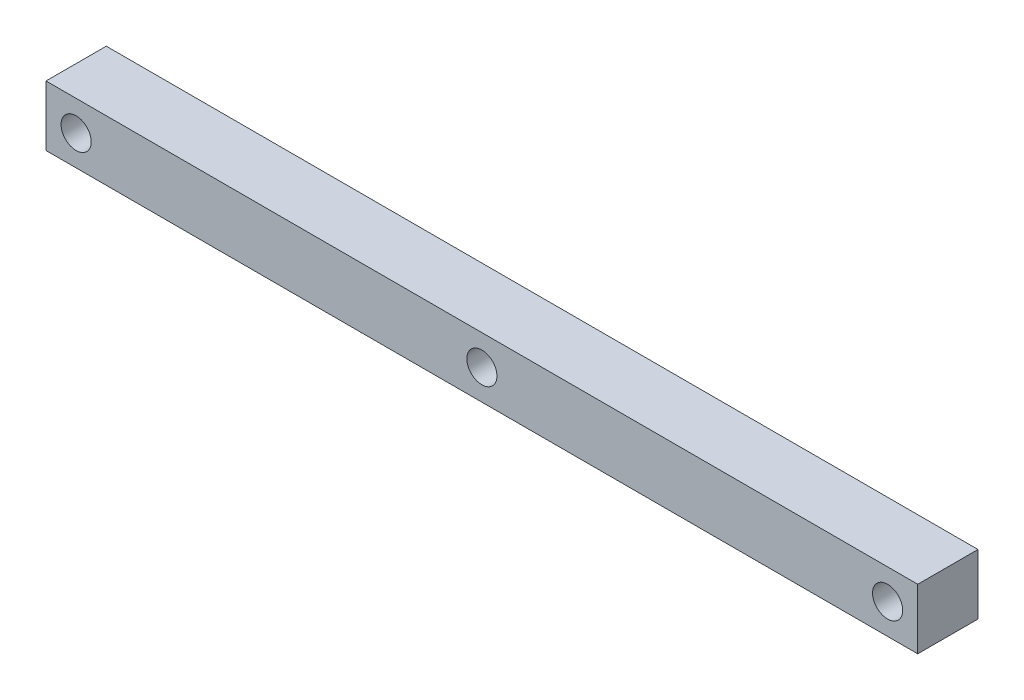
SolidWorks part; units mm, degrees
material "1060 Alloy for 162A"
ref_plane "Front Plane" through (0, 0, 0) normal (0, 0, 1) x (1, 0, 0)
ref_plane "Top Plane" through (0, 0, 0) normal (0, 1, 0) x (1, 0, 0)
ref_plane "Right Plane" through (0, 0, 0) normal (1, 0, 0) x (0, 0, -1)
sketch "Sketch1" plane through (0, 0, 0) normal (0, 0, 1) x (1, 0, 0)
  line L0 (202, 0) -> (-202, 0) construction
  line L1 (217, 15) -> (-217, 15)
  line L2 (217, 15) -> (217, -15)
  line L3 (217, -15) -> (-217, -15)
  line L4 (-217, 15) -> (-217, -15)
  line L5 (217, 15) -> (-217, -15) construction
  line L6 (217, -15) -> (-217, 15) construction
  circle A0 centre (-202, 0) radius 7.5
  circle A1 centre (202, 0) radius 7.5
  circle A2 centre (0, 0) radius 7.5
  point P0 (0, 0)
  point P8 (0, 0)
  dimension "D2" = 15
  dimension "D1" = 30
  dimension "D3" = 404
  dimension "D4" = 15
extrude "Boss-Extrude1" add sketch "Sketch1" along normal mid plane 30
equation "\"A\"= 202"
equation "\"hole_diameter\"=15"
equation "\"D2@Sketch1\"=\"hole_diameter\""
equation "\"D3@Sketch1\"=2*\"A\""
equation "\"D4@Sketch1\"=\"hole_diameter\""
